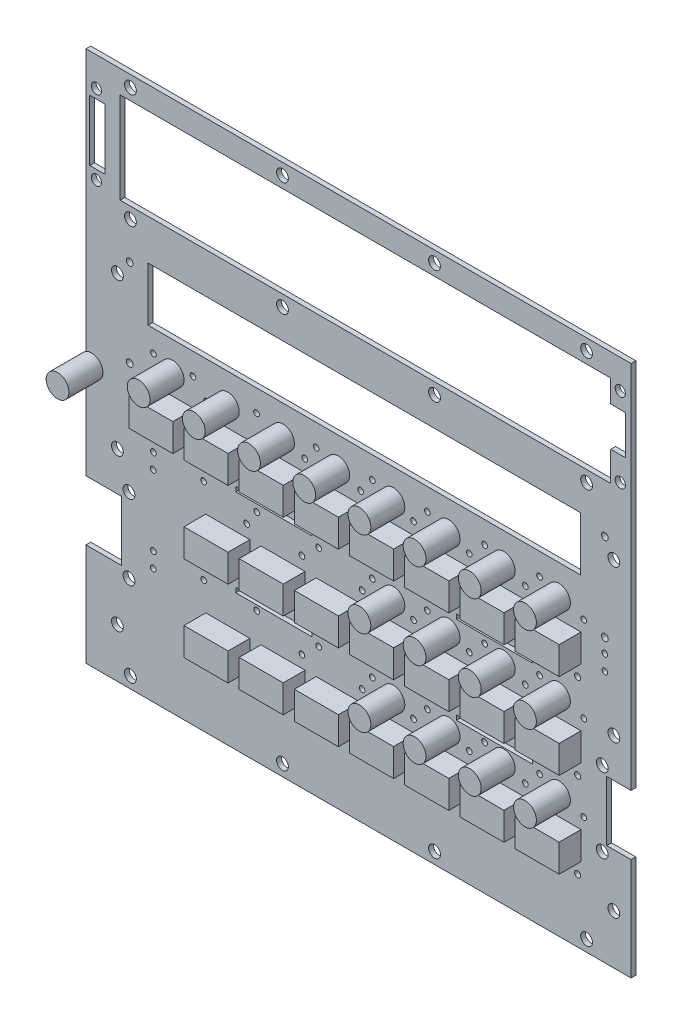
SolidWorks part; units mm, degrees
ref_plane "Front Plane" through (0, 0, 0) normal (0, 0, 1) x (1, 0, 0)
ref_plane "Top Plane" through (0, 0, 0) normal (0, 1, 0) x (1, 0, 0)
ref_plane "Right Plane" through (0, 0, 0) normal (1, 0, 0) x (0, 0, -1)
sketch "Sketch1" plane through (0, 0, 0) normal (0, 0, 1) x (1, 0, 0)
  line L0 (0, 0) -> (182.118, 0)
  line L1 (182.118, 0) -> (182.118, 34.2468)
  line L2 (182.118, 34.2468) -> (173.9875, 34.2468)
  line L3 (173.9875, 34.2468) -> (173.9875, 54.2468)
  line L4 (173.9875, 54.2468) -> (182.118, 54.2468)
  line L5 (182.118, 54.2468) -> (182.118, 177.8)
  line L6 (182.118, 177.8) -> (0, 177.8)
  line L7 (0, 177.8) -> (0, 54.2468)
  line L8 (0, 54.2468) -> (11.8694, 54.2468)
  line L9 (11.8694, 54.2468) -> (11.8694, 34.2468)
  line L10 (11.8694, 34.2468) -> (0, 34.2468)
  line L11 (0, 34.2468) -> (0, 0)
  line L12 (20.7391, 108.1786) -> (20.7391, 126.1796)
  line L13 (20.7391, 126.1796) -> (165.3007, 126.1796)
  line L14 (165.3007, 126.1796) -> (165.3007, 108.1786)
  line L15 (165.3007, 108.1786) -> (20.7391, 108.1786)
  line L16 (1.27, 144.653) -> (1.27, 164.973)
  line L17 (1.27, 164.973) -> (6.35, 164.973)
  line L18 (6.35, 164.973) -> (6.35, 144.653)
  line L19 (6.35, 144.653) -> (1.27, 144.653)
  line L20 (12.7, 170.18) -> (175.26, 170.18)
  line L21 (175.26, 170.18) -> (175.26, 162.6616)
  line L22 (175.26, 162.6616) -> (180.086, 162.6616)
  line L23 (180.086, 162.6616) -> (180.2892, 162.4584)
  line L24 (180.2892, 162.4584) -> (180.2892, 149.606)
  line L25 (180.2892, 149.606) -> (175.3616, 149.606)
  line L26 (175.3616, 149.606) -> (175.26, 149.5044)
  line L27 (175.26, 149.5044) -> (175.26, 139.7)
  line L28 (175.26, 139.7) -> (12.7, 139.7)
  line L29 (12.7, 139.7) -> (11.43, 139.7)
  line L30 (11.43, 139.7) -> (11.43, 170.18)
  line L31 (11.43, 170.18) -> (12.7, 170.18)
  line L32 (50.0634, 45.4152) -> (50.0634, 47.0027)
  line L33 (50.0634, 47.0027) -> (75.4634, 47.0027)
  line L34 (75.4634, 47.0027) -> (75.4634, 45.4152)
  line L35 (75.4634, 45.4152) -> (50.0634, 45.4152)
  line L36 (123.8134, 45.4152) -> (123.8134, 47.0027)
  line L37 (123.8134, 47.0027) -> (149.2134, 47.0027)
  line L38 (149.2134, 47.0027) -> (149.2134, 45.4152)
  line L39 (149.2134, 45.4152) -> (123.8134, 45.4152)
  line L40 (123.8134, 74.6252) -> (123.8134, 76.2127)
  line L41 (123.8134, 76.2127) -> (149.2134, 76.2127)
  line L42 (149.2134, 76.2127) -> (149.2134, 74.6252)
  line L43 (149.2134, 74.6252) -> (123.8134, 74.6252)
  line L44 (50.0634, 74.6252) -> (50.0634, 76.2127)
  line L45 (50.0634, 76.2127) -> (75.4634, 76.2127)
  line L46 (75.4634, 76.2127) -> (75.4634, 74.6252)
  line L47 (75.4634, 74.6252) -> (50.0634, 74.6252)
extrude "BOARD" add sketch "Sketch1" along normal blind 1.5921 separate body
ref_plane "Plane1" through (0, 0, 1.5921) normal (0, 0, 1) x (1, 0, 0)
sketch "Sketch2" plane through (0, 0, 1.5921) normal (0, 0, 1) x (1, 0, 0)
  circle A0 centre (1.8694, 86.9188) radius 3.81
extrude "LED-KINGBRIGHT_3P_2P54-1" add sketch "Sketch2" along normal blind 11.3538 separate body
sketch "Sketch3" plane through (0, 0, 1.5921) normal (0, 0, 1) x (1, 0, 0)
  circle A0 centre (158.0312, 41.1988) radius 3.81
extrude "LED-KINGBRIGHT_3P_2P54-2" add sketch "Sketch3" along normal blind 11.3538 separate body
sketch "Sketch4" plane through (0, 0, 1.5921) normal (0, 0, 1) x (1, 0, 0)
  circle A0 centre (139.5937, 41.1988) radius 3.81
extrude "LED-KINGBRIGHT_3P_2P54-3" add sketch "Sketch4" along normal blind 11.3538 separate body
sketch "Sketch5" plane through (0, 0, 1.5921) normal (0, 0, 1) x (1, 0, 0)
  circle A0 centre (121.1562, 41.1988) radius 3.81
extrude "LED-KINGBRIGHT_3P_2P54-4" add sketch "Sketch5" along normal blind 11.3538 separate body
sketch "Sketch6" plane through (0, 0, 1.5921) normal (0, 0, 1) x (1, 0, 0)
  circle A0 centre (102.7187, 41.1988) radius 3.81
extrude "LED-KINGBRIGHT_3P_2P54-5" add sketch "Sketch6" along normal blind 11.3538 separate body
sketch "Sketch7" plane through (0, 0, 1.5921) normal (0, 0, 1) x (1, 0, 0)
  circle A0 centre (158.0312, 69.7738) radius 3.81
extrude "LED-KINGBRIGHT_3P_2P54-6" add sketch "Sketch7" along normal blind 11.3538 separate body
sketch "Sketch8" plane through (0, 0, 1.5921) normal (0, 0, 1) x (1, 0, 0)
  circle A0 centre (139.5937, 69.7738) radius 3.81
extrude "LED-KINGBRIGHT_3P_2P54-7" add sketch "Sketch8" along normal blind 11.3538 separate body
sketch "Sketch9" plane through (0, 0, 1.5921) normal (0, 0, 1) x (1, 0, 0)
  circle A0 centre (121.1562, 69.7738) radius 3.81
extrude "LED-KINGBRIGHT_3P_2P54-8" add sketch "Sketch9" along normal blind 11.3538 separate body
sketch "Sketch10" plane through (0, 0, 1.5921) normal (0, 0, 1) x (1, 0, 0)
  circle A0 centre (102.7187, 69.7738) radius 3.81
extrude "LED-KINGBRIGHT_3P_2P54-9" add sketch "Sketch10" along normal blind 11.3538 separate body
sketch "Sketch19" plane through (0, 0, 1.5921) normal (0, 0, 1) x (1, 0, 0)
  circle A0 centre (158.0312, 98.3488) radius 3.81
extrude "LED-KINGBRIGHT_3P_2P54-18" add sketch "Sketch19" along normal blind 11.3538 separate body
sketch "Sketch20" plane through (0, 0, 1.5921) normal (0, 0, 1) x (1, 0, 0)
  circle A0 centre (139.5937, 98.3488) radius 3.81
extrude "LED-KINGBRIGHT_3P_2P54-19" add sketch "Sketch20" along normal blind 11.3538 separate body
sketch "Sketch21" plane through (0, 0, 1.5921) normal (0, 0, 1) x (1, 0, 0)
  circle A0 centre (121.1562, 98.3488) radius 3.81
extrude "LED-KINGBRIGHT_3P_2P54-20" add sketch "Sketch21" along normal blind 11.3538 separate body
sketch "Sketch22" plane through (0, 0, 1.5921) normal (0, 0, 1) x (1, 0, 0)
  circle A0 centre (102.7187, 98.3488) radius 3.81
extrude "LED-KINGBRIGHT_3P_2P54-21" add sketch "Sketch22" along normal blind 11.3538 separate body
sketch "Sketch23" plane through (0, 0, 1.5921) normal (0, 0, 1) x (1, 0, 0)
  circle A0 centre (84.2812, 98.3488) radius 3.81
extrude "LED-KINGBRIGHT_3P_2P54-22" add sketch "Sketch23" along normal blind 11.3538 separate body
sketch "Sketch24" plane through (0, 0, 1.5921) normal (0, 0, 1) x (1, 0, 0)
  circle A0 centre (65.8437, 98.3488) radius 3.81
extrude "LED-KINGBRIGHT_3P_2P54-23" add sketch "Sketch24" along normal blind 11.3538 separate body
sketch "Sketch25" plane through (0, 0, 1.5921) normal (0, 0, 1) x (1, 0, 0)
  circle A0 centre (47.4062, 98.3488) radius 3.81
extrude "LED-KINGBRIGHT_3P_2P54-24" add sketch "Sketch25" along normal blind 11.3538 separate body
sketch "Sketch26" plane through (0, 0, 1.5921) normal (0, 0, 1) x (1, 0, 0)
  circle A0 centre (28.9687, 98.3488) radius 3.81
extrude "LED-KINGBRIGHT_3P_2P54-25" add sketch "Sketch26" along normal blind 11.3538 separate body
sketch "Sketch27" plane through (0, 0, 1.5921) normal (0, 0, 1) x (1, 0, 0)
  line L0 (150.6652, 25.3238) -> (150.6652, 34.5948)
  line L1 (150.6652, 34.5948) -> (165.3972, 34.5948)
  line L2 (165.3972, 34.5948) -> (165.3972, 25.3238)
  line L3 (165.3972, 25.3238) -> (150.6652, 25.3238)
extrude "SWITCH-MCDTS2-1" add sketch "Sketch27" along normal blind 7.3 separate body
sketch "Sketch28" plane through (0, 0, 1.5921) normal (0, 0, 1) x (1, 0, 0)
  line L0 (150.6652, 53.8988) -> (150.6652, 63.1698)
  line L1 (150.6652, 63.1698) -> (165.3972, 63.1698)
  line L2 (165.3972, 63.1698) -> (165.3972, 53.8988)
  line L3 (165.3972, 53.8988) -> (150.6652, 53.8988)
extrude "SWITCH-MCDTS2-2" add sketch "Sketch28" along normal blind 7.3 separate body
sketch "Sketch29" plane through (0, 0, 1.5921) normal (0, 0, 1) x (1, 0, 0)
  line L0 (132.2277, 25.3238) -> (132.2277, 34.5948)
  line L1 (132.2277, 34.5948) -> (146.9597, 34.5948)
  line L2 (146.9597, 34.5948) -> (146.9597, 25.3238)
  line L3 (146.9597, 25.3238) -> (132.2277, 25.3238)
extrude "SWITCH-MCDTS2-3" add sketch "Sketch29" along normal blind 7.3 separate body
sketch "Sketch30" plane through (0, 0, 1.5921) normal (0, 0, 1) x (1, 0, 0)
  line L0 (113.7902, 25.3238) -> (113.7902, 34.5948)
  line L1 (113.7902, 34.5948) -> (128.5222, 34.5948)
  line L2 (128.5222, 34.5948) -> (128.5222, 25.3238)
  line L3 (128.5222, 25.3238) -> (113.7902, 25.3238)
extrude "SWITCH-MCDTS2-4" add sketch "Sketch30" along normal blind 7.3 separate body
sketch "Sketch31" plane through (0, 0, 1.5921) normal (0, 0, 1) x (1, 0, 0)
  line L0 (95.3527, 25.3238) -> (95.3527, 34.5948)
  line L1 (95.3527, 34.5948) -> (110.0847, 34.5948)
  line L2 (110.0847, 34.5948) -> (110.0847, 25.3238)
  line L3 (110.0847, 25.3238) -> (95.3527, 25.3238)
extrude "SWITCH-MCDTS2-5" add sketch "Sketch31" along normal blind 7.3 separate body
sketch "Sketch32" plane through (0, 0, 1.5921) normal (0, 0, 1) x (1, 0, 0)
  line L0 (76.9152, 25.3238) -> (76.9152, 34.5948)
  line L1 (76.9152, 34.5948) -> (91.6472, 34.5948)
  line L2 (91.6472, 34.5948) -> (91.6472, 25.3238)
  line L3 (91.6472, 25.3238) -> (76.9152, 25.3238)
extrude "SWITCH-MCDTS2-6" add sketch "Sketch32" along normal blind 7.3 separate body
sketch "Sketch33" plane through (0, 0, 1.5921) normal (0, 0, 1) x (1, 0, 0)
  line L0 (58.4777, 25.3238) -> (58.4777, 34.5948)
  line L1 (58.4777, 34.5948) -> (73.2097, 34.5948)
  line L2 (73.2097, 34.5948) -> (73.2097, 25.3238)
  line L3 (73.2097, 25.3238) -> (58.4777, 25.3238)
extrude "SWITCH-MCDTS2-7" add sketch "Sketch33" along normal blind 7.3 separate body
sketch "Sketch34" plane through (0, 0, 1.5921) normal (0, 0, 1) x (1, 0, 0)
  line L0 (40.0402, 25.3238) -> (40.0402, 34.5948)
  line L1 (40.0402, 34.5948) -> (54.7722, 34.5948)
  line L2 (54.7722, 34.5948) -> (54.7722, 25.3238)
  line L3 (54.7722, 25.3238) -> (40.0402, 25.3238)
extrude "SWITCH-MCDTS2-8" add sketch "Sketch34" along normal blind 7.3 separate body
sketch "Sketch36" plane through (0, 0, 1.5921) normal (0, 0, 1) x (1, 0, 0)
  line L0 (132.2277, 53.8988) -> (132.2277, 63.1698)
  line L1 (132.2277, 63.1698) -> (146.9597, 63.1698)
  line L2 (146.9597, 63.1698) -> (146.9597, 53.8988)
  line L3 (146.9597, 53.8988) -> (132.2277, 53.8988)
extrude "SWITCH-MCDTS2-10" add sketch "Sketch36" along normal blind 7.3 separate body
sketch "Sketch37" plane through (0, 0, 1.5921) normal (0, 0, 1) x (1, 0, 0)
  line L0 (113.7902, 53.8988) -> (113.7902, 63.1698)
  line L1 (113.7902, 63.1698) -> (128.5222, 63.1698)
  line L2 (128.5222, 63.1698) -> (128.5222, 53.8988)
  line L3 (128.5222, 53.8988) -> (113.7902, 53.8988)
extrude "SWITCH-MCDTS2-11" add sketch "Sketch37" along normal blind 7.3 separate body
sketch "Sketch38" plane through (0, 0, 1.5921) normal (0, 0, 1) x (1, 0, 0)
  line L0 (95.3527, 53.8988) -> (95.3527, 63.1698)
  line L1 (95.3527, 63.1698) -> (110.0847, 63.1698)
  line L2 (110.0847, 63.1698) -> (110.0847, 53.8988)
  line L3 (110.0847, 53.8988) -> (95.3527, 53.8988)
extrude "SWITCH-MCDTS2-12" add sketch "Sketch38" along normal blind 7.3 separate body
sketch "Sketch39" plane through (0, 0, 1.5921) normal (0, 0, 1) x (1, 0, 0)
  line L0 (76.9152, 53.8988) -> (76.9152, 63.1698)
  line L1 (76.9152, 63.1698) -> (91.6472, 63.1698)
  line L2 (91.6472, 63.1698) -> (91.6472, 53.8988)
  line L3 (91.6472, 53.8988) -> (76.9152, 53.8988)
extrude "SWITCH-MCDTS2-13" add sketch "Sketch39" along normal blind 7.3 separate body
sketch "Sketch40" plane through (0, 0, 1.5921) normal (0, 0, 1) x (1, 0, 0)
  line L0 (58.4777, 53.8988) -> (58.4777, 63.1698)
  line L1 (58.4777, 63.1698) -> (73.2097, 63.1698)
  line L2 (73.2097, 63.1698) -> (73.2097, 53.8988)
  line L3 (73.2097, 53.8988) -> (58.4777, 53.8988)
extrude "SWITCH-MCDTS2-14" add sketch "Sketch40" along normal blind 7.3 separate body
sketch "Sketch41" plane through (0, 0, 1.5921) normal (0, 0, 1) x (1, 0, 0)
  line L0 (40.0402, 53.8988) -> (40.0402, 63.1698)
  line L1 (40.0402, 63.1698) -> (54.7722, 63.1698)
  line L2 (54.7722, 63.1698) -> (54.7722, 53.8988)
  line L3 (54.7722, 53.8988) -> (40.0402, 53.8988)
extrude "SWITCH-MCDTS2-15" add sketch "Sketch41" along normal blind 7.3 separate body
sketch "Sketch43" plane through (0, 0, 1.5921) normal (0, 0, 1) x (1, 0, 0)
  line L0 (150.6652, 82.4738) -> (150.6652, 91.7448)
  line L1 (150.6652, 91.7448) -> (165.3972, 91.7448)
  line L2 (165.3972, 91.7448) -> (165.3972, 82.4738)
  line L3 (165.3972, 82.4738) -> (150.6652, 82.4738)
extrude "SWITCH-MCDTS2-17" add sketch "Sketch43" along normal blind 7.3 separate body
sketch "Sketch44" plane through (0, 0, 1.5921) normal (0, 0, 1) x (1, 0, 0)
  line L0 (132.2277, 82.4738) -> (132.2277, 91.7448)
  line L1 (132.2277, 91.7448) -> (146.9597, 91.7448)
  line L2 (146.9597, 91.7448) -> (146.9597, 82.4738)
  line L3 (146.9597, 82.4738) -> (132.2277, 82.4738)
extrude "SWITCH-MCDTS2-18" add sketch "Sketch44" along normal blind 7.3 separate body
sketch "Sketch45" plane through (0, 0, 1.5921) normal (0, 0, 1) x (1, 0, 0)
  line L0 (113.7902, 82.4738) -> (113.7902, 91.7448)
  line L1 (113.7902, 91.7448) -> (128.5222, 91.7448)
  line L2 (128.5222, 91.7448) -> (128.5222, 82.4738)
  line L3 (128.5222, 82.4738) -> (113.7902, 82.4738)
extrude "SWITCH-MCDTS2-19" add sketch "Sketch45" along normal blind 7.3 separate body
sketch "Sketch46" plane through (0, 0, 1.5921) normal (0, 0, 1) x (1, 0, 0)
  line L0 (95.3527, 82.4738) -> (95.3527, 91.7448)
  line L1 (95.3527, 91.7448) -> (110.0847, 91.7448)
  line L2 (110.0847, 91.7448) -> (110.0847, 82.4738)
  line L3 (110.0847, 82.4738) -> (95.3527, 82.4738)
extrude "SWITCH-MCDTS2-20" add sketch "Sketch46" along normal blind 7.3 separate body
sketch "Sketch47" plane through (0, 0, 1.5921) normal (0, 0, 1) x (1, 0, 0)
  line L0 (76.9152, 82.4738) -> (76.9152, 91.7448)
  line L1 (76.9152, 91.7448) -> (91.6472, 91.7448)
  line L2 (91.6472, 91.7448) -> (91.6472, 82.4738)
  line L3 (91.6472, 82.4738) -> (76.9152, 82.4738)
extrude "SWITCH-MCDTS2-21" add sketch "Sketch47" along normal blind 7.3 separate body
sketch "Sketch48" plane through (0, 0, 1.5921) normal (0, 0, 1) x (1, 0, 0)
  line L0 (58.4777, 82.4738) -> (58.4777, 91.7448)
  line L1 (58.4777, 91.7448) -> (73.2097, 91.7448)
  line L2 (73.2097, 91.7448) -> (73.2097, 82.4738)
  line L3 (73.2097, 82.4738) -> (58.4777, 82.4738)
extrude "SWITCH-MCDTS2-22" add sketch "Sketch48" along normal blind 7.3 separate body
sketch "Sketch49" plane through (0, 0, 1.5921) normal (0, 0, 1) x (1, 0, 0)
  line L0 (40.0402, 82.4738) -> (40.0402, 91.7448)
  line L1 (40.0402, 91.7448) -> (54.7722, 91.7448)
  line L2 (54.7722, 91.7448) -> (54.7722, 82.4738)
  line L3 (54.7722, 82.4738) -> (40.0402, 82.4738)
extrude "SWITCH-MCDTS2-23" add sketch "Sketch49" along normal blind 7.3 separate body
sketch "Sketch50" plane through (0, 0, 1.5921) normal (0, 0, 1) x (1, 0, 0)
  line L0 (21.6027, 82.4738) -> (21.6027, 91.7448)
  line L1 (21.6027, 91.7448) -> (36.3347, 91.7448)
  line L2 (36.3347, 91.7448) -> (36.3347, 82.4738)
  line L3 (36.3347, 82.4738) -> (21.6027, 82.4738)
extrude "SWITCH-MCDTS2-24" add sketch "Sketch50" along normal blind 7.3 separate body
sketch "Sketch52" plane through (0, 0, 1.5921) normal (0, 0, 1) x (1, 0, 0)
  line L0 (0, 34.2468) -> (0, 0) construction
  line L1 (0, 0) -> (182.118, 0) construction
  circle B0 centre (164.2745, 21.1074) radius 1.016
  circle B1 centre (164.2745, 49.6824) radius 1.016
  circle B2 centre (145.8341, 21.8186) radius 0.9652
  circle B3 centre (127.4191, 21.6154) radius 0.9652
  circle B4 centre (108.9787, 21.7424) radius 0.9652
  circle B5 centre (90.5383, 21.844) radius 0.9652
  circle B6 centre (72.0979, 20.7772) radius 0.9652
  circle B7 centre (53.6575, 21.1582) radius 0.9652
  circle B8 centre (35.2187, 21.1328) radius 1.016
  circle B9 centre (145.8341, 49.5554) radius 1.016
  circle B10 centre (127.3937, 49.3522) radius 1.016
  circle B11 centre (108.9533, 49.1236) radius 1.016
  circle B12 centre (90.5129, 49.6824) radius 1.016
  circle B13 centre (72.0725, 49.1998) radius 1.016
  circle B14 centre (53.6321, 49.1998) radius 1.016
  circle B15 centre (35.1917, 49.276) radius 1.016
  circle B16 centre (164.2745, 78.2574) radius 1.016
  circle B17 centre (145.8341, 77.7748) radius 1.016
  circle B18 centre (127.3175, 78.3336) radius 1.016
  circle B19 centre (108.9533, 78.74) radius 1.016
  circle B20 centre (90.5129, 78.3336) radius 1.016
  circle B21 centre (72.0725, 78.2574) radius 1.016
  circle B22 centre (53.6321, 78.4098) radius 1.016
  circle B23 centre (35.1917, 78.0542) radius 1.016
  circle B24 centre (92.2655, 38.6588) radius 0.9525
  circle B25 centre (77.7367, 43.7388) radius 0.9525
  circle B26 centre (72.1487, 38.6588) radius 0.9525
  circle B27 centre (57.0611, 43.7388) radius 0.9525
  circle B28 centre (39.3065, 43.7388) radius 0.9525
  circle B29 centre (22.4663, 38.6588) radius 0.9525
  circle B30 centre (22.5425, 43.7388) radius 0.9525
  circle B31 centre (77.7367, 72.3138) radius 0.9525
  circle B32 centre (92.2655, 67.2338) radius 0.9525
  circle B33 centre (72.1487, 67.2338) radius 0.9525
  circle B34 centre (57.0611, 72.3138) radius 0.9525
  circle B35 centre (53.7083, 67.2338) radius 0.9525
  circle B36 centre (39.3065, 72.3138) radius 0.9525
  circle B37 centre (22.4663, 67.2338) radius 0.9525
  circle B38 centre (22.5425, 72.3138) radius 0.9525
  circle B39 centre (166.3065, 95.8088) radius 0.9525
  circle B40 centre (151.5491, 100.8888) radius 0.9525
  circle B41 centre (146.7993, 95.8088) radius 0.9525
  circle B42 centre (133.1849, 100.8888) radius 0.9525
  circle B43 centre (114.0587, 100.8888) radius 0.9525
  circle B44 centre (128.0795, 95.8088) radius 0.9525
  circle B45 centre (109.4359, 95.8088) radius 0.9525
  circle B46 centre (95.6691, 100.8888) radius 0.9525
  circle B47 centre (91.7575, 95.8088) radius 0.9525
  circle B48 centre (76.9493, 100.8888) radius 0.9525
  circle B49 centre (73.1139, 95.8088) radius 0.9525
  circle B50 centre (56.9849, 100.8888) radius 0.9525
  circle B51 centre (40.2971, 95.8088) radius 0.9525
  circle B52 centre (35.7505, 100.8888) radius 0.9525
  circle B53 centre (24.7777, 95.8088) radius 0.9525
  circle B54 centre (22.5425, 100.8888) radius 0.9525
  circle B55 centre (133.1849, 72.3138) radius 0.9525
  circle B56 centre (146.7993, 67.2338) radius 0.9525
  circle B57 centre (114.0587, 72.3138) radius 0.9525
  circle B58 centre (128.0795, 67.2338) radius 0.9525
  circle B59 centre (95.6691, 72.3138) radius 0.9525
  circle B60 centre (109.4359, 67.2338) radius 0.9525
  circle B61 centre (151.5491, 43.7388) radius 0.9525
  circle B62 centre (133.1849, 43.7388) radius 0.9525
  circle B63 centre (114.0587, 43.7388) radius 0.9525
  circle B64 centre (95.6691, 43.7388) radius 0.9525
  circle B65 centre (109.4359, 38.6588) radius 0.9525
  circle B66 centre (151.5491, 72.3138) radius 0.9525
  circle B67 centre (166.3065, 67.2338) radius 0.9525
  circle B68 centre (173.3296, 89.4588) radius 0.9525
  circle B69 centre (173.355, 84.3534) radius 0.9525
  circle B70 centre (176.3725, 118.11) radius 1.9685
  circle B71 centre (176.3725, 67.31) radius 1.9685
  circle B72 centre (176.3725, 16.51) radius 1.9685
  circle B73 centre (167.259, 135.89) radius 1.9685
  circle B74 centre (116.459, 135.89) radius 1.9685
  circle B75 centre (65.659, 135.89) radius 1.9685
  circle B76 centre (14.859, 135.89) radius 1.9685
  circle B77 centre (10.5105, 118.11) radius 1.9685
  circle B78 centre (10.5105, 67.31) radius 1.9685
  circle B79 centre (10.5105, 16.51) radius 1.9685
  circle B80 centre (166.3065, 38.6588) radius 0.9525
  circle B81 centre (146.7993, 38.6588) radius 0.9525
  circle B82 centre (128.0795, 38.6588) radius 0.9525
  circle B83 centre (14.859, 173.99) radius 1.9685
  circle B84 centre (65.659, 173.99) radius 1.9685
  circle B85 centre (116.459, 173.99) radius 1.9685
  circle B86 centre (167.259, 173.99) radius 1.9685
  circle B87 centre (167.259, 3.81) radius 1.9685
  circle B88 centre (116.459, 3.81) radius 1.9685
  circle B89 centre (65.659, 3.81) radius 1.9685
  circle B90 centre (14.859, 3.81) radius 1.9685
  circle B91 centre (172.5066, 56.7436) radius 1.9685
  circle B92 centre (172.5066, 31.75) radius 1.9685
  circle B93 centre (14.3688, 56.7436) radius 1.9685
  circle B94 centre (14.3688, 31.75) radius 1.9685
  circle B95 centre (173.3575, 123.3754) radius 1.1303
  circle B96 centre (173.3575, 94.1654) radius 1.1303
  circle B97 centre (14.6075, 94.1654) radius 1.1303
  circle B98 centre (14.6075, 123.3754) radius 1.1303
  circle B99 centre (178.5137, 141.5618) radius 1.7145
  circle B100 centre (178.5137, 168.0616) radius 1.7145
  circle B101 centre (3.5001, 168.0616) radius 1.7145
  circle B102 centre (3.5001, 141.5618) radius 1.7145
  dimension "D1" = 14.859
  dimension "D2" = 3.81
sketch_block_instance "Block9-1"
sketch_block "Block1"
extrude "Cut-Extrude1" cut sketch "Sketch52" against normal blind 12.7
